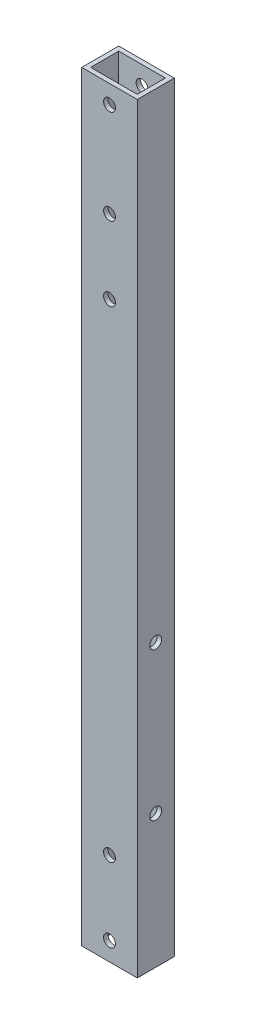
SolidWorks part; units mm, degrees
ref_plane "正面" through (0, 0, 0) normal (0, 0, 1) x (1, 0, 0)
ref_plane "平面" through (0, 0, 0) normal (0, 1, 0) x (1, 0, 0)
ref_plane "右側面" through (0, 0, 0) normal (1, 0, 0) x (0, 0, -1)
sketch "ｽｹｯﾁ1" plane through (0, 0, 0) normal (0, 1, 0) x (1, 0, 0)
  line L0 (-6.3, 3.8) -> (6.3, 3.8)
  line L1 (-7.5, 5) -> (7.5, 5)
  line L2 (-7.5, 5) -> (-7.5, -5)
  line L3 (-7.5, -5) -> (7.5, -5)
  line L4 (7.5, 5) -> (7.5, -5)
  line L5 (-7.5, 5) -> (7.5, -5) construction
  line L6 (-7.5, -5) -> (7.5, 5) construction
  line L7 (6.3, 3.8) -> (6.3, -3.8)
  line L8 (-6.3, -3.8) -> (6.3, -3.8)
  line L9 (-6.3, 3.8) -> (-6.3, -3.8)
  point P0 (0, 0)
  dimension "D1" = 15
  dimension "D2" = 10
  dimension "D3" = 1.2
extrude "ﾎﾞｽ - 押し出し1" add sketch "ｽｹｯﾁ1" along normal mid plane 220
sketch "ｽｹｯﾁ2" plane through (0, 0, -5) normal (0, 0, -1) x (-1, 0, 0)
  line L0 (0, -110) -> (0, -85) construction
  line L1 (-7.5, -110) -> (7.5, -110) construction
  circle A0 centre (0, -85) radius 1.6
  circle A1 centre (0, -105) radius 1.6
  dimension "D2" = 3.2
  dimension "D3" = 3.2
  dimension "D1" = 25
  dimension "D4" = 20
extrude "ｶｯﾄ - 押し出し1" cut sketch "ｽｹｯﾁ2" against normal blind 100
sketch "ｽｹｯﾁ3" plane through (7.5, 0, 0) normal (1, 0, 0) x (0, 0, -1)
  line L1 (0, -110) -> (0, 0) construction
  line L2 (-5, -110) -> (5, -110) construction
  line L4 (6.5084, -36.5) -> (31.5068, -36.5)
  line L5 (31.5068, -36.5) -> (31.5068, -31.5)
  line L6 (31.5068, -31.5) -> (6.5084, -31.5)
  line L7 (6.5084, -31.5) -> (6.5084, -36.5)
  line L8 (6.5084, -36.5) -> (31.5068, -36.5) construction
  line L10 (31.5068, -31.5) -> (6.5084, -31.5) construction
  line L11 (6.5084, -31.5) -> (6.5084, -36.5) construction
  line L12 (6.5084, -76.5) -> (31.5068, -76.5)
  line L13 (31.5068, -76.5) -> (31.5068, -71.5)
  line L14 (31.5068, -71.5) -> (6.5084, -71.5)
  line L15 (6.5084, -71.5) -> (6.5084, -76.5)
  line L16 (6.5084, -76.5) -> (31.5068, -76.5) construction
  line L18 (31.5068, -71.5) -> (6.5084, -71.5) construction
  line L19 (6.5084, -71.5) -> (6.5084, -76.5) construction
  line L26 (31.5068, -36.5) -> (31.5068, -31.5)
  line L27 (31.5068, -76.5) -> (31.5068, -71.5)
  circle A0 centre (0, -34) radius 1.6
  circle A1 centre (0, -74) radius 1.6
  dimension "D3" = 3.2
  dimension "D4" = 3.2
  dimension "D5" = 36
  dimension "D6" = 40
  dimension "D1" = 0
  dimension "D2" = 0
extrude "ｶｯﾄ - 押し出し2" cut sketch "ｽｹｯﾁ3" against normal blind 15 contours A0 | A1
sketch "ｽｹｯﾁ4" plane through (0, 0, -5) normal (0, 0, -1) x (-1, 0, 0)
  line L2 (0, 0) -> (0, 65) construction
  circle A0 centre (0, 65) radius 1.6
  circle A1 centre (0, 45) radius 1.6
  dimension "D1" = 65
  dimension "D2" = 3.2
  dimension "D3" = 3.2
  dimension "D4" = 20
extrude "ｶｯﾄ - 押し出し3" cut sketch "ｽｹｯﾁ4" against normal blind 10
sketch "ｽｹｯﾁ5" plane through (0, 110, 0) normal (0, 1, 0) x (1, 0, 0)
  line L4 (7.5, -5) -> (7.5, 5)
  line L5 (7.5, 5) -> (-7.5, 5)
  line L6 (-7.5, 5) -> (-7.5, -5)
  line L7 (-7.5, -5) -> (7.5, -5)
  line L8 (7.5, -5) -> (7.5, 5)
  line L9 (7.5, 5) -> (-7.5, 5)
  line L10 (-7.5, 5) -> (-7.5, -5)
  line L11 (-7.5, -5) -> (7.5, -5)
  dimension "D1" = 0
extrude "ｶｯﾄ - 押し出し4" cut sketch "ｽｹｯﾁ5" against normal blind 14.5
sketch "ｽｹｯﾁ6" plane through (0, 0, -5) normal (0, 0, -1) x (-1, 0, 0)
  line L0 (0, 95.5) -> (0, 90.5) construction
  line L1 (-7.5, 95.5) -> (7.5, 95.5) construction
  circle A0 centre (0, 90.5) radius 1.6
  dimension "D2" = 3.2
  dimension "D1" = 5
extrude "ｶｯﾄ - 押し出し5" cut sketch "ｽｹｯﾁ6" against normal blind 15
